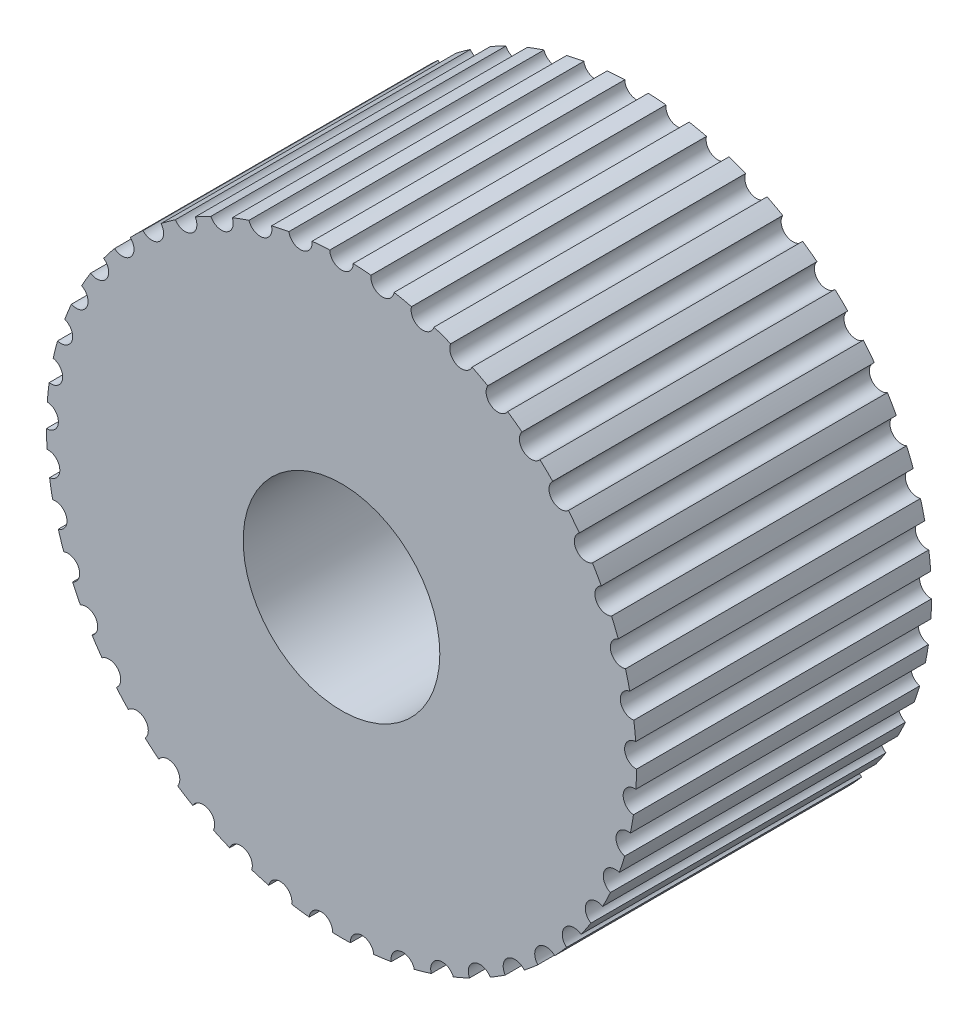
SolidWorks part; units mm, degrees
ref_plane "Front Plane" through (0, 0, 0) normal (0, 0, 1) x (1, 0, 0)
ref_plane "Top Plane" through (0, 0, 0) normal (0, 1, 0) x (1, 0, 0)
ref_plane "Right Plane" through (0, 0, 0) normal (1, 0, 0) x (0, 0, -1)
sketch "Sketch1" plane through (0, 0, 0) normal (0, 0, 1) x (1, 0, 0)
  circle A0 centre (0, 0) radius 15
extrude "Boss-Extrude1" add sketch "Sketch1" along normal blind 15
sketch "Sketch2" plane through (0, 0, 15) normal (0, 0, 1) x (1, 0, 0)
  circle A0 centre (0, 0) radius 5
extrude "Cut-Extrude1" cut sketch "Sketch2" against normal blind 15
sketch "Sketch3" plane through (0, 0, 15) normal (0, 0, 1) x (1, 0, 0)
  circle A0 centre (0, 15) radius 0.5958
  circle A1 centre (0, 0) radius 15 construction
  circle A2 centre (2.0876, 14.854) radius 0.5958
  circle A3 centre (4.1346, 14.4189) radius 0.5958
  circle A4 centre (6.101, 13.7032) radius 0.5958
  circle A5 centre (7.9488, 12.7207) radius 0.5958
  circle A6 centre (9.6418, 11.4907) radius 0.5958
  circle A7 centre (11.1472, 10.037) radius 0.5958
  circle A8 centre (12.4356, 8.3879) radius 0.5958
  circle A9 centre (13.4819, 6.5756) radius 0.5958
  circle A10 centre (14.2658, 4.6353) radius 0.5958
  circle A11 centre (14.7721, 2.6047) radius 0.5958
  circle A12 centre (14.9909, 0.5235) radius 0.5958
  circle A13 centre (14.9178, -1.5679) radius 0.5958
  circle A14 centre (14.5544, -3.6288) radius 0.5958
  circle A15 centre (13.9078, -5.6191) radius 0.5958
  circle A16 centre (12.9904, -7.5) radius 0.5958
  circle A17 centre (11.8202, -9.2349) radius 0.5958
  circle A18 centre (10.4199, -10.7901) radius 0.5958
  circle A19 centre (8.8168, -12.1353) radius 0.5958
  circle A20 centre (7.0421, -13.2442) radius 0.5958
  circle A21 centre (5.1303, -14.0954) radius 0.5958
  circle A22 centre (3.1187, -14.6722) radius 0.5958
  circle A23 centre (1.0463, -14.9635) radius 0.5958
  circle A24 centre (-1.0463, -14.9635) radius 0.5958
  circle A25 centre (-3.1187, -14.6722) radius 0.5958
  circle A26 centre (-5.1303, -14.0954) radius 0.5958
  circle A27 centre (-7.0421, -13.2442) radius 0.5958
  circle A28 centre (-8.8168, -12.1353) radius 0.5958
  circle A29 centre (-10.4199, -10.7901) radius 0.5958
  circle A30 centre (-11.8202, -9.2349) radius 0.5958
  circle A31 centre (-12.9904, -7.5) radius 0.5958
  circle A32 centre (-13.9078, -5.6191) radius 0.5958
  circle A33 centre (-14.5544, -3.6288) radius 0.5958
  circle A34 centre (-14.9178, -1.5679) radius 0.5958
  circle A35 centre (-14.9909, 0.5235) radius 0.5958
  circle A36 centre (-14.7721, 2.6047) radius 0.5958
  circle A37 centre (-14.2658, 4.6353) radius 0.5958
  circle A38 centre (-13.4819, 6.5756) radius 0.5958
  circle A39 centre (-12.4356, 8.3879) radius 0.5958
  circle A40 centre (-11.1472, 10.037) radius 0.5958
  circle A41 centre (-9.6418, 11.4907) radius 0.5958
  circle A42 centre (-7.9488, 12.7207) radius 0.5958
  circle A43 centre (-6.101, 13.7032) radius 0.5958
  circle A44 centre (-4.1346, 14.4189) radius 0.5958
  circle A45 centre (-2.0876, 14.854) radius 0.5958
  point P94 (0, 0)
  dimension "D1" = 45
extrude "Cut-Extrude2" cut sketch "Sketch3" against normal blind 15
